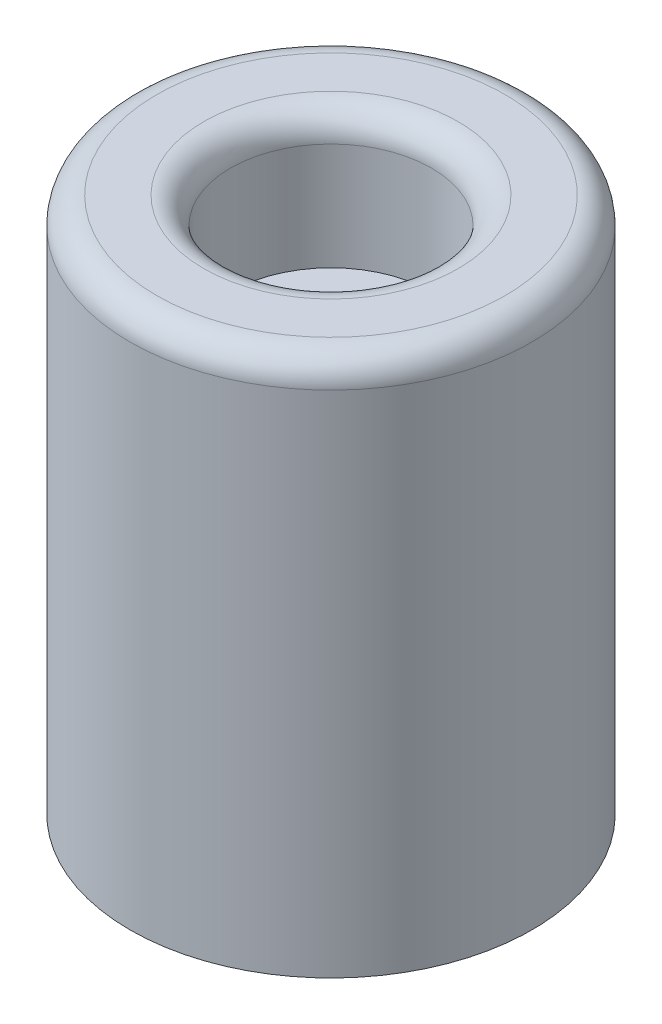
SolidWorks part; units mm, degrees
material "Rubber"
ref_plane "Front" through (0, 0, 0) normal (0, 0, 1) x (1, 0, 0)
ref_plane "Top" through (0, 0, 0) normal (0, 1, 0) x (1, 0, 0)
ref_plane "Right" through (0, 0, 0) normal (1, 0, 0) x (0, 0, -1)
sketch "Sketch1" plane through (0, 0, 0) normal (0, 1, 0) x (1, 0, 0)
  circle A0 centre (0, 0) radius 9.525
  dimension "D1" = 19.05
extrude "Boss-Extrude1" add sketch "Sketch1" along normal blind 25.4
sketch "Sketch2" plane through (0, 25.4, 0) normal (0, 1, 0) x (1, 0, 0)
  circle A0 centre (0, 0) radius 4.7625
  dimension "D1" = 9.525
extrude "Cut-Extrude1" cut sketch "Sketch2" against normal blind 6.35
sketch "Sketch3" plane through (0, 19.05, 0) normal (0, 1, 0) x (1, 0, 0)
  circle A0 centre (0, 0) radius 1.9844
  dimension "D1" = 3.9688
extrude "Cut-Extrude2" cut sketch "Sketch3" against normal through all
fillet "Fillet1" radius 1.27 2 edges at (0, 25.4, 4.7625) (0, 25.4, 9.525)
